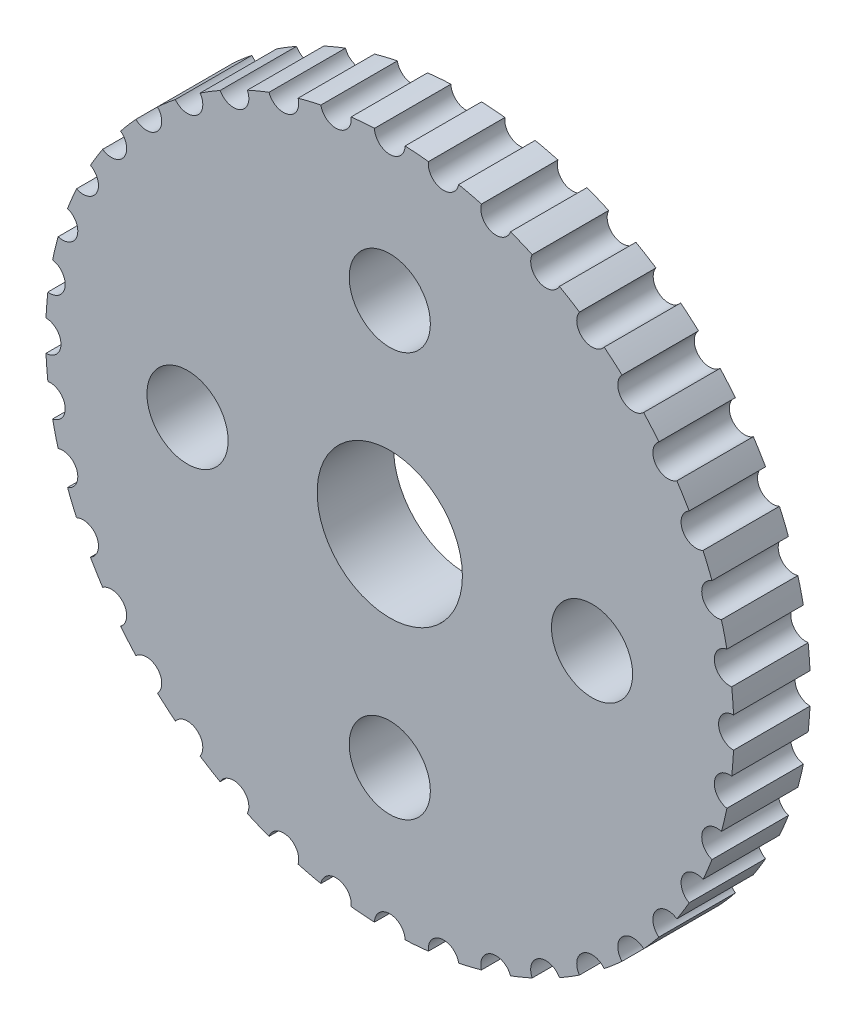
SolidWorks part; units mm, degrees
material "延性铁"
ref_plane "前视基准面" through (0, 0, 0) normal (0, 0, 1) x (1, 0, 0)
ref_plane "上视基准面" through (0, 0, 0) normal (0, 1, 0) x (1, 0, 0)
ref_plane "右视基准面" through (0, 0, 0) normal (1, 0, 0) x (0, 0, -1)
sketch "草图8" plane through (0, 0, 0) normal (0, 0, 1) x (1, 0, 0)
  circle A0 centre (0, 0) radius 45
  circle A1 centre (0, 45) radius 2
  circle A2 centre (7.0396, 44.446) radius 2
  circle A3 centre (13.9058, 42.7975) radius 2
  circle A4 centre (20.4296, 40.0953) radius 2
  circle A5 centre (26.4503, 36.4058) radius 2
  circle A6 centre (31.8198, 31.8198) radius 2
  circle A7 centre (36.4058, 26.4503) radius 2
  circle A8 centre (40.0953, 20.4296) radius 2
  circle A9 centre (42.7975, 13.9058) radius 2
  circle A10 centre (44.446, 7.0396) radius 2
  circle A11 centre (45, 0) radius 2
  circle A12 centre (44.446, -7.0396) radius 2
  circle A13 centre (42.7975, -13.9058) radius 2
  circle A14 centre (40.0953, -20.4296) radius 2
  circle A15 centre (36.4058, -26.4503) radius 2
  circle A16 centre (31.8198, -31.8198) radius 2
  circle A17 centre (26.4503, -36.4058) radius 2
  circle A18 centre (20.4296, -40.0953) radius 2
  circle A19 centre (13.9058, -42.7975) radius 2
  circle A20 centre (7.0396, -44.446) radius 2
  circle A21 centre (0, -45) radius 2
  circle A22 centre (-7.0396, -44.446) radius 2
  circle A23 centre (-13.9058, -42.7975) radius 2
  circle A24 centre (-20.4296, -40.0953) radius 2
  circle A25 centre (-26.4503, -36.4058) radius 2
  circle A26 centre (-31.8198, -31.8198) radius 2
  circle A27 centre (-36.4058, -26.4503) radius 2
  circle A28 centre (-40.0953, -20.4296) radius 2
  circle A29 centre (-42.7975, -13.9058) radius 2
  circle A30 centre (-44.446, -7.0396) radius 2
  circle A31 centre (-45, 0) radius 2
  circle A32 centre (-44.446, 7.0396) radius 2
  circle A33 centre (-42.7975, 13.9058) radius 2
  circle A34 centre (-40.0953, 20.4296) radius 2
  circle A35 centre (-36.4058, 26.4503) radius 2
  circle A36 centre (-31.8198, 31.8198) radius 2
  circle A37 centre (-26.4503, 36.4058) radius 2
  circle A38 centre (-20.4296, 40.0953) radius 2
  circle A39 centre (-13.9058, 42.7975) radius 2
  circle A40 centre (-7.0396, 44.446) radius 2
  circle A41 centre (0, 26.4503) radius 5.3086
  circle A42 centre (26.4503, 0) radius 5.3086
  circle A43 centre (0, -26.4503) radius 5.3086
  circle A44 centre (-26.4503, 0) radius 5.3086
  circle A45 centre (0, 0) radius 9.5
  point P85 (0, 0)
  point P95 (0, 0)
  dimension "D1" = 40
  dimension "D2" = 4
extrude "凸台-拉伸1" add sketch "草图8" along normal blind 10 contours A40 A0 A39 A38 A37 A36 A35 A34 A33 A32 A31 A30 A29 A28 A27 A26 A25 A24 A23 A22 A21 A20 A19 A18 A17 A16 A15
sketch "草图9" plane through (0, 0, 10) normal (0, 0, 1) x (1, 0, 0)
  circle A0 centre (0, 0) radius 45
  circle A2 centre (1.6279, 21.3976) radius 0.0001
  circle A3 centre (-26.4963, 0.0222) radius 5.3597
  circle A4 centre (-0.0138, -26.451) radius 5.2948
  circle A5 centre (31.6383, -0.7552) radius 0.0659
  circle A6 centre (8.3104, -4.7902) radius 0.0921
